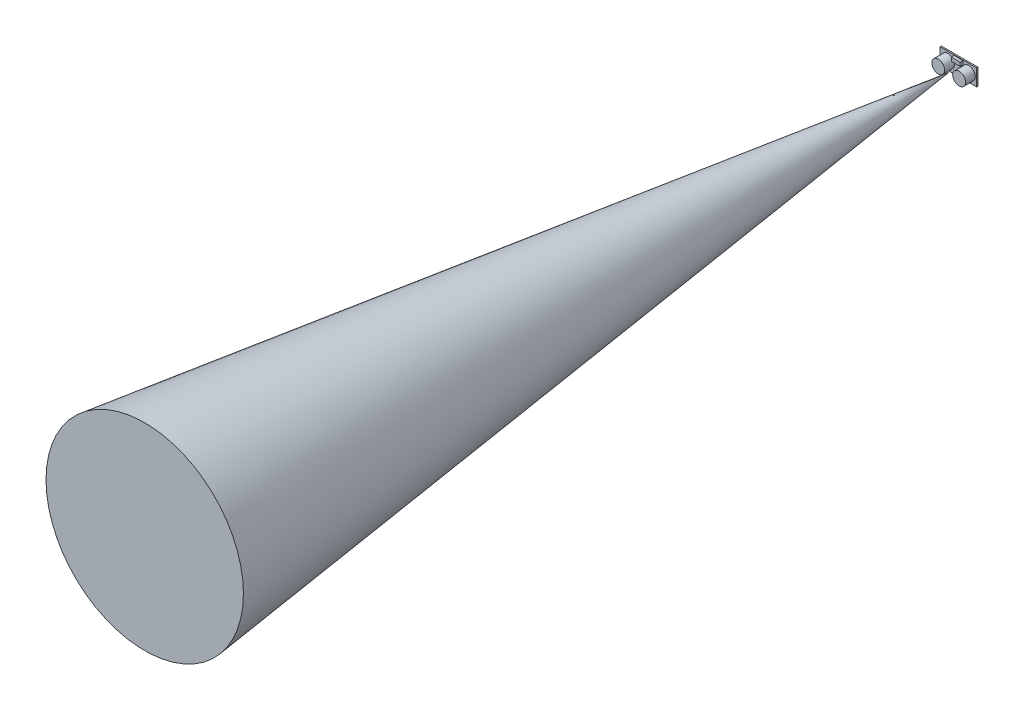
SolidWorks part; units mm, degrees
ref_plane "Ebene vorne" through (0, 0, 0) normal (0, 0, 1) x (1, 0, 0)
ref_plane "Ebene oben" through (0, 0, 0) normal (0, 1, 0) x (1, 0, 0)
ref_plane "Ebene rechts" through (0, 0, 0) normal (1, 0, 0) x (0, 0, -1)
sketch "Skizze1" plane through (0, 0, 0) normal (0, 0, 1) x (1, 0, 0)
  line L1 (0, 0) -> (45.5, 0)
  line L2 (0, 0) -> (0, 20.6)
  line L3 (0, 20.6) -> (45.5, 20.6)
  line L4 (45.5, 0) -> (45.5, 20.6)
  dimension "D1" = 20.6
  dimension "D2" = 45.5
extrude "Aufsatz-Linear austragen1" add sketch "Skizze1" against normal blind 1.6
sketch "Skizze2" plane through (0, 0, 0) normal (0, 0, 1) x (1, 0, 0)
  line L0 (22.75, 20.6) -> (22.75, 0) construction
  line L1 (45.5, 20.6) -> (0, 20.6) construction
  line L2 (0, 0) -> (45.5, 0) construction
  line L3 (0, 10.3) -> (45.5, 10.3) construction
  line L4 (0, 20.6) -> (0, 0) construction
  line L5 (45.5, 0) -> (45.5, 20.6) construction
  circle A0 centre (9.75, 10.3) radius 8
  circle A1 centre (35.75, 10.3) radius 8
  point P16 (0, 0)
  point P17 (0, 0)
  dimension "D1" = 16
  dimension "D2" = 26
extrude "Aufsatz-Linear austragen2" add sketch "Skizze2" along normal blind 12.1
sketch "Skizze3" plane through (0, 0, 0) normal (0, 0, 1) x (1, 0, 0)
  line L0 (22.75, 20.6) -> (22.75, 0) construction
  line L1 (45.5, 20.6) -> (0, 20.6) construction
  line L2 (0, 0) -> (45.5, 0) construction
  line L4 (17.25, 19.9) -> (28.25, 19.9)
  line L5 (17.25, 19.9) -> (17.25, 15.3)
  line L6 (17.25, 15.3) -> (28.25, 15.3)
  line L7 (28.25, 19.9) -> (28.25, 15.3)
  line L8 (17.25, 19.9) -> (28.25, 15.3) construction
  line L9 (17.25, 15.3) -> (28.25, 19.9) construction
  point P6 (22.75, 17.6)
  dimension "D1" = 4.6
  dimension "D2" = 11
  dimension "D3" = 5.3
extrude "Aufsatz-Linear austragen3" add sketch "Skizze3" along normal blind 3.4
sketch "Skizze4" plane through (0, 0, -1.6) normal (0, 0, -1) x (-1, 0, 0)
  line L0 (-22.75, 20.6) -> (-22.75, 0) construction
  line L1 (-45.5, 20.6) -> (0, 20.6) construction
  line L2 (0, 0) -> (-45.5, 0) construction
  line L3 (-26.55, 2.3) -> (-18.95, 2.3) construction
  line L5 (-26.9, 1.95) -> (-26.2, 1.95)
  line L6 (-26.9, 1.95) -> (-26.9, 2.65)
  line L7 (-26.9, 2.65) -> (-26.2, 2.65)
  line L8 (-26.2, 1.95) -> (-26.2, 2.65)
  line L9 (-26.9, 1.95) -> (-26.2, 2.65) construction
  line L10 (-26.9, 2.65) -> (-26.2, 1.95) construction
  line L11 (-24.3667, 1.95) -> (-23.6667, 1.95)
  line L12 (-24.3667, 1.95) -> (-24.3667, 2.65)
  line L13 (-24.3667, 2.65) -> (-23.6667, 2.65)
  line L14 (-23.6667, 1.95) -> (-23.6667, 2.65)
  line L15 (-24.3667, 1.95) -> (-23.6667, 2.65) construction
  line L16 (-24.3667, 2.65) -> (-23.6667, 1.95) construction
  line L17 (-21.8333, 1.95) -> (-21.1333, 1.95)
  line L18 (-21.8333, 1.95) -> (-21.8333, 2.65)
  line L19 (-21.8333, 2.65) -> (-21.1333, 2.65)
  line L20 (-21.1333, 1.95) -> (-21.1333, 2.65)
  line L21 (-21.8333, 1.95) -> (-21.1333, 2.65) construction
  line L22 (-21.8333, 2.65) -> (-21.1333, 1.95) construction
  line L23 (-19.3, 1.95) -> (-18.6, 1.95)
  line L24 (-19.3, 1.95) -> (-19.3, 2.65)
  line L25 (-19.3, 2.65) -> (-18.6, 2.65)
  line L26 (-18.6, 1.95) -> (-18.6, 2.65)
  line L27 (-19.3, 1.95) -> (-18.6, 2.65) construction
  line L28 (-19.3, 2.65) -> (-18.6, 1.95) construction
  point P12 (-24.0167, 2.3)
  point P17 (-21.4833, 2.3)
  point P26 (0, 0)
  point P27 (0, 0)
  dimension "D1" = 0.7
  dimension "D2" = 8.3
  dimension "D3" = 2.65
  dimension "D4" = 2.5333
extrude "Aufsatz-Linear austragen4" add sketch "Skizze4" along normal blind 6.4
sketch "Skizze5" plane through (0, 1.95, 0) normal (0, -1, 0) x (1, 0, 0)
  line L0 (26.9, -8) -> (26.9, -1.6) construction
  line L1 (26.2, -8) -> (26.9, -8)
  line L2 (26.2, -8) -> (26.2, -7.3)
  line L3 (26.2, -7.3) -> (26.9, -7.3)
  line L4 (26.9, -8) -> (26.9, -7.3)
  line L5 (24.3667, -8) -> (24.3667, -1.6) construction
  line L6 (23.6667, -8) -> (24.3667, -8)
  line L7 (23.6667, -8) -> (23.6667, -7.3)
  line L8 (23.6667, -7.3) -> (24.3667, -7.3)
  line L9 (24.3667, -8) -> (24.3667, -7.3)
  line L10 (21.8333, -8) -> (21.8333, -1.6) construction
  line L11 (21.1333, -8) -> (21.8333, -8)
  line L12 (21.1333, -8) -> (21.1333, -7.3)
  line L13 (21.1333, -7.3) -> (21.8333, -7.3)
  line L14 (21.8333, -8) -> (21.8333, -7.3)
  line L15 (19.3, -8) -> (19.3, -1.6) construction
  line L16 (18.6, -8) -> (19.3, -8)
  line L17 (18.6, -8) -> (18.6, -7.3)
  line L18 (18.6, -7.3) -> (19.3, -7.3)
  line L19 (19.3, -8) -> (19.3, -7.3)
extrude "Aufsatz-Linear austragen5" add sketch "Skizze5" along normal blind 6.9
ref_plane "Ebene1" through (22.75, 0, 0) normal (-1, 0, 0) x (0, 0, 1)
sketch "Skizze6" plane through (22.75, 0, 0) normal (-1, 0, 0) x (0, 0, 1)
  line L0 (12.1, 10.3) -> (1012.1, 10.3)
  line L1 (12.1, 2.3) -> (12.1, 18.3) construction
  line L2 (1012.1, 10.3) -> (1012.1, -112.4846)
  line L3 (1012.1, -112.4846) -> (12.1, 10.3)
  line L4 (12.1, 10.3) -> (118.1554, 10.3) construction
  point P4 (112.1, 10.3)
  point P7 (118.1554, 10.3)
  dimension "D1" = 7
  dimension "D2" = 1000
revolve "Rotation2" add sketch "Skizze6" angle 360 about L4
